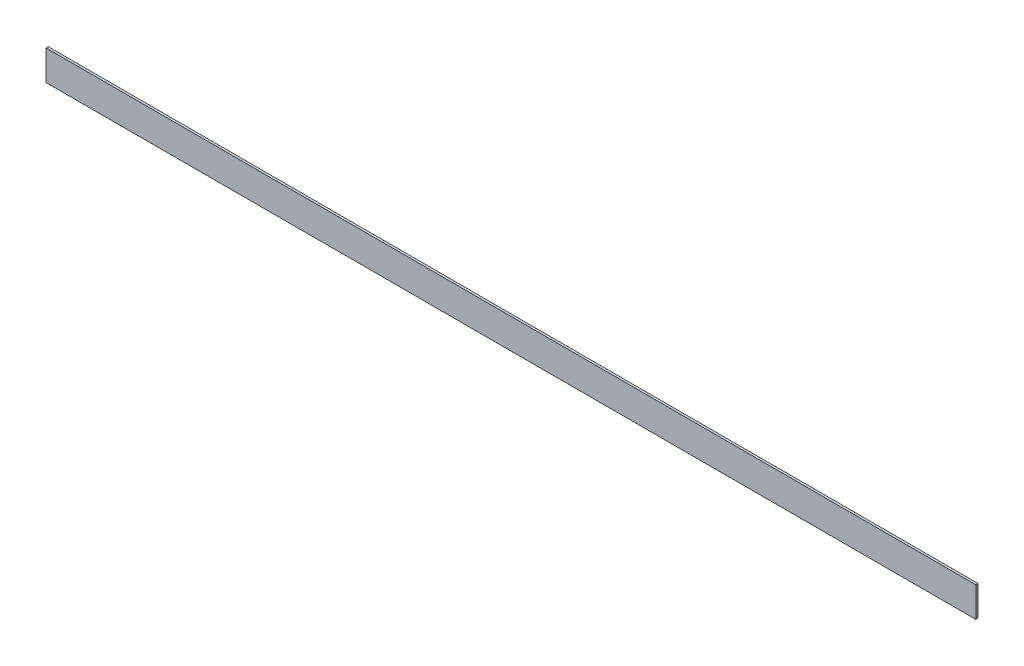
SolidWorks part; units mm, degrees
ref_plane "Front Plane" through (0, 0, 0) normal (0, 0, 1) x (1, 0, 0)
ref_plane "Top Plane" through (0, 0, 0) normal (0, 1, 0) x (1, 0, 0)
ref_plane "Right Plane" through (0, 0, 0) normal (1, 0, 0) x (0, 0, -1)
other "Configuration Table"
sketch "Sketch1" plane through (0, 0, 0) normal (0, 0, 1) x (1, 0, 0)
  line L1 (40, 1052) -> (660, 1052)
  line L2 (40, 1052) -> (40, 1072)
  line L3 (40, 1072) -> (660, 1072)
  line L4 (660, 1052) -> (660, 1072)
extrude "PRESS_tepsi_rafi_raf_buk_arka_1" add sketch "Sketch1" against normal blind 1.5 from offset 798.5 separate body
